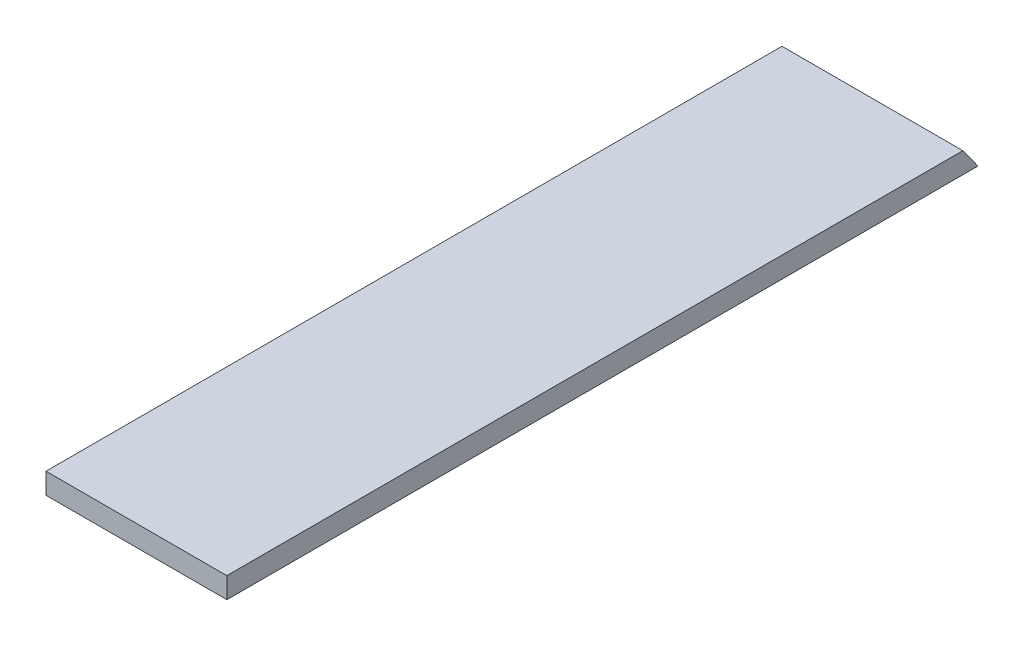
SolidWorks part; units mm, degrees
ref_plane "Спереди" through (0, 0, 0) normal (0, 0, 1) x (1, 0, 0)
ref_plane "Сверху" through (0, 0, 0) normal (0, 1, 0) x (1, 0, 0)
ref_plane "Справа" through (0, 0, 0) normal (1, 0, 0) x (0, 0, -1)
sketch "Эскиз1" plane through (0, 0, 0) normal (1, 0, 0) x (0, 0, -1)
  line L0 (54, 0) -> (-54, 0)
  line L1 (-54, 0) -> (-54, 3)
  line L2 (-54, 3) -> (51.8204, 3)
  line L3 (51.8204, 3) -> (54, 0)
  line L4 (54, 0) -> (54, 39.2101) construction
  dimension "D1" = 108
  dimension "D2" = 36
  dimension "D3" = 3
extrude "Бобышка-Вытянуть1" add sketch "Эскиз1" along normal blind 26
